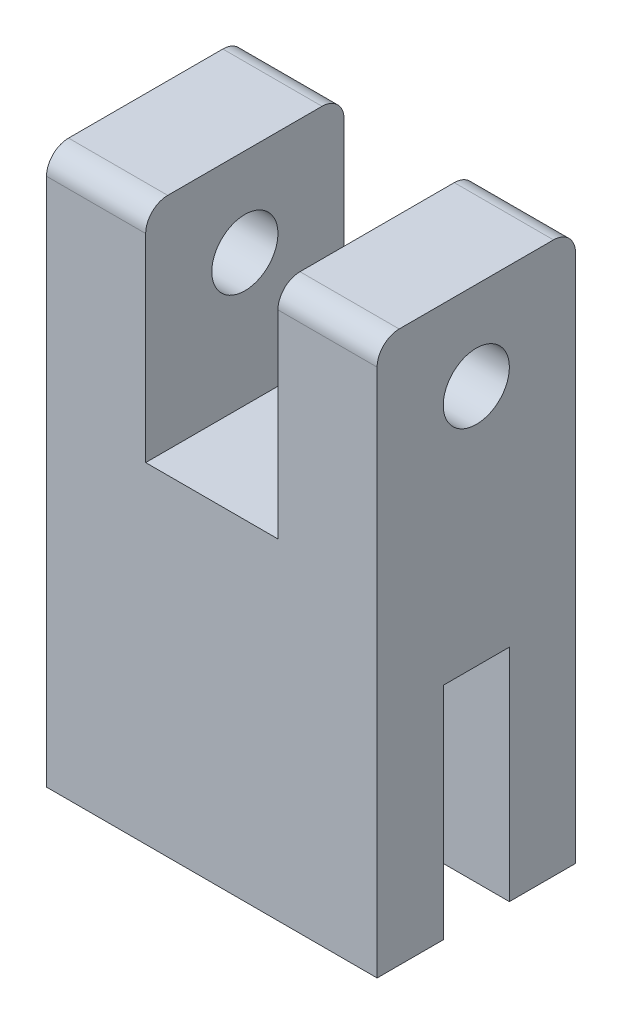
SolidWorks part; units mm, degrees
ref_plane "Alzado" through (0, 0, 0) normal (0, 0, 1) x (1, 0, 0)
ref_plane "Planta" through (0, 0, 0) normal (0, 1, 0) x (1, 0, 0)
ref_plane "Vista lateral" through (0, 0, 0) normal (1, 0, 0) x (0, 0, -1)
sketch "Croquis2" plane through (0, 0, 0) normal (0, 0, 1) x (1, 0, 0)
  line L1 (-7.5, 7.5) -> (7.5, 7.5)
  line L2 (-7.5, 7.5) -> (-7.5, -7.5)
  line L3 (-7.5, -7.5) -> (7.5, -7.5)
  line L4 (7.5, 7.5) -> (7.5, -7.5)
  point P4 (0, -7.5)
  point P6 (7.5, 0)
  dimension "D1" = 15
  dimension "D2" = 15
extrude "Saliente-Extruir1" add sketch "Croquis2" along normal mid plane 9
sketch "Croquis3" plane through (0, 0, 0) normal (0, 0, 1) x (1, 0, 0)
  line L0 (-7.5, 7.5) -> (-7.5, -7.5) construction
  line L1 (-7.5, 2.5) -> (7.5, 2.5)
  line L2 (-7.5, 2.5) -> (-7.5, -7.5)
  line L3 (-7.5, -7.5) -> (7.5, -7.5)
  line L4 (7.5, 2.5) -> (7.5, -7.5)
  line L5 (7.5, 7.5) -> (-7.5, 7.5) construction
  dimension "D1" = 5
extrude "Cortar-Extruir1" cut sketch "Croquis3" against normal mid plane 3
sketch "Croquis4" plane through (0, 0, 0) normal (0, 0, 1) x (1, 0, 0)
  line L0 (7.5, 7.5) -> (-7.5, 7.5) construction
  line L1 (-1.5, 0) -> (-1.5, -7.5)
  line L2 (-7.5, -7.5) -> (7.5, -7.5) construction
  line L3 (1.5, 0) -> (1.5, -7.5)
  line L4 (-1.5, -7.5) -> (1.5, -7.5)
  arc A0 (1.5, 0) -> (-1.5, 0) centre (0, 0) ccw
  dimension "D2" = 3
  dimension "D1" = 7.5
extrude "Cortar-Extruir2" cut sketch "Croquis4" against normal through all
sketch "Croquis10" plane through (0, 7.5, 0) normal (0, 1, 0) x (1, 0, 0)
  line L0 (-3, 4.5) -> (-3, -4.5)
  line L1 (3, 4.5) -> (3, -4.5)
  line L2 (0, 4.5) -> (0, -4.5) construction
  line L3 (-3, 4.5) -> (-7.5, 4.5)
  line L4 (7.5, 4.5) -> (-7.5, 4.5)
  line L5 (-7.5, 4.5) -> (-7.5, -4.5)
  line L6 (-7.5, -4.5) -> (7.5, -4.5)
  line L7 (7.5, -4.5) -> (7.5, 4.5)
  line L8 (7.5, 4.5) -> (3, 4.5)
  line L9 (-7.5, 4.5) -> (-7.5, -4.5)
  line L10 (-7.5, -4.5) -> (-3, -4.5)
  line L11 (7.5, -4.5) -> (7.5, 4.5)
  line L12 (3, -4.5) -> (7.5, -4.5)
  line L13 (7.5, 4.5) -> (-7.5, 4.5) construction
  point P11 (0, 0)
  dimension "D2" = 6
  dimension "D1" = 0
extrude "Saliente-Extruir4" add sketch "Croquis10" along normal blind 10
sketch "Croquis7" plane through (0, 0, 0) normal (1, 0, 0) x (0, 0, -1)
  line L1 (-4.5, 17.5) -> (4.5, 17.5) construction
  circle A0 centre (0, 13.5) radius 1.5
  dimension "D1" = 3
  dimension "D2" = 4
extrude "Cortar-Extruir3" cut sketch "Croquis7" against normal through all both and the other way through all
fillet "Redondeo2" radius 1 4 edges at (5.25, 17.5, -4.5) (5.25, 17.5, 4.5) (-5.25, 17.5, 4.5) (-5.25, 17.5, -4.5)
